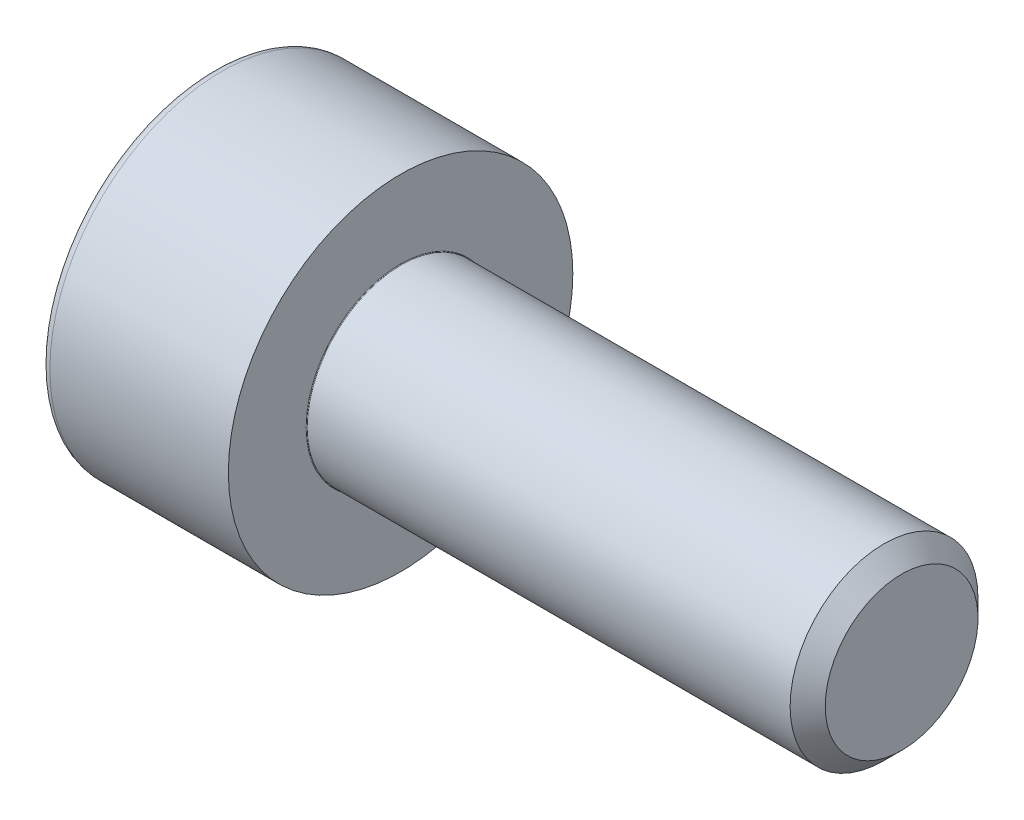
SolidWorks part; units mm, degrees
material "AISI 304"
ref_plane "Plane1" through (0, 0, 0) normal (0, 0, 1) x (1, 0, 0)
ref_plane "Plane2" through (0, 0, 0) normal (0, 1, 0) x (1, 0, 0)
ref_plane "Plane3" through (0, 0, 0) normal (1, 0, 0) x (0, 0, -1)
other "55"
sketch "BodySke" plane through (0, 0, 0) normal (0, 0, 1) x (1, 0, 0)
  line L0 (0, 0) -> (0, 2.75)
  line L1 (0, 2.75) -> (3, 2.75)
  line L2 (3, 2.75) -> (3, 1.5)
  line L3 (3, 1.5) -> (10.7195, 1.5)
  line L4 (11, 1.2195) -> (11, 0)
  line L5 (11, 0) -> (0, 0)
  line L6 (-31.75, 0) -> (127, 0) construction
  line L8 (11, 1.2195) -> (10.7195, 1.5)
  line L10 (11, -1.2195) -> (10.7195, -1.5) construction
  line L11 (3.5, 9.525) -> (3.5, 3.175) construction
  line L12 (3, 9.525) -> (3, 3.175) construction
  line L13 (-49, 9.525) -> (-49, 3.175) construction
  dimension "Head_ht" = 3
  dimension "Length" = 8
  dimension "Body_ch_ang" = 45
  dimension "Diameter" = 3
  dimension "Minor_dia" = 2.439
  dimension "Advance" = 0.5
  dimension "Thread_nom" = 8
  dimension "Thread_length" = 60
  dimension "Head_dia" = 5.5
revolve "Base-Revolve" add sketch "BodySke" angle 360 about L6
cosmetic thread "ThreadCosmetic" parameters "Thread_length"=6.5, "Thread_minor"=2.439
fillet "Fillet1" radius 0.01 1 edges at (3, 0, 1.5)
fillet "Fillet2" radius 0.15 1 edges at (0, 0, 2.75)
sketch "Sketch2" plane through (0, 0, 0) normal (0, 0, 1) x (1, 0, 0)
  line L0 (0, 1.28) -> (1.3, 1.28)
  line L1 (1.3, 1.28) -> (2.039, 0)
  line L2 (-31.75, 0) -> (127, 0) construction
  line L3 (2.039, 0) -> (0, 0)
  line L4 (0, 0) -> (0, 1.28)
  line L6 (0, 0) -> (47.625, 0) construction
  dimension "D1" = 1.28
  dimension "D2" = 60
  dimension "Depth" = 1.3
revolve "Hex-PreBroach" cut sketch "Sketch2" angle 360 about L6
sketch "Sketch3" plane through (0, 0, 0) normal (-1, 0, 0) x (0, 0.5, 0.866)
  line L0 (0.739, 1.28) -> (-0.739, 1.28)
  line L1 (-0.739, 1.28) -> (-1.478, 0)
  line L2 (0.739, 1.28) -> (1.478, 0)
  line L3 (0.739, -1.28) -> (1.478, 0)
  line L4 (0.739, -1.28) -> (-0.739, -1.28)
  line L5 (-0.739, -1.28) -> (-1.478, 0)
  dimension "D1" = 1.28
  dimension "D2" = 1.28
  dimension "Hex_size" = 2.56
extrude "Hex" cut sketch "Sketch3" against normal blind 1.3
sketch "ThdSchSke" plane through (0, 0, 0) normal (0, 0, 1) x (1, 0, 0)
  line L0 (4.5, -1.2195) -> (4.3036, -1.5)
  line L1 (4.5, -1.2195) -> (4.6964, -1.5)
  line L2 (4.6964, -1.5) -> (4.6964, -1.875)
  line L3 (-3.175, 0) -> (5.1513, 0) construction
  line L4 (0, 2.6) -> (0, -2.6) construction
  line L5 (4.6964, -1.875) -> (4.3036, -1.875)
  line L6 (4.3036, -1.875) -> (4.3036, -1.5)
  dimension "Thread_minor" = 2.439
  dimension "Diameter" = 3
  dimension "SideAngle" = 55
  dimension "VeeAngle" = 70
  dimension "Overcut" = 3.75
  dimension "Start" = 4.5
revolve "ThreadSchematic" [suppressed] cut sketch "ThdSchSke" angle 360 about L3
pattern_linear "ThdSchPat" [suppressed]
equation "\"D2@Sketch3\" = \"Hex_size@Sketch3\" / 2"
equation "\"D1@Sketch3\" = \"Hex_size@Sketch3\" / 2"
equation "\"D1@Sketch2\" = \"Hex_size@Sketch3\" / 2"
equation "\"Thread_minor@ThreadCosmetic\"  =  \"Minor_dia@BodySke\""
equation "\"Depth@Sketch2\" =  \"Key_eng@Hex\""
equation "\"Thread_length@ThreadCosmetic\" = ((sgn( (\"Length@BodySke\" - \"Advance@BodySke\" * 3.0) - \"Thread_nom@BodySke\" )-1)*( (\"Length@BodySke\" - \"Advance@BodySke\" * 3.0) - \"Thread_nom@BodySke\" ))/-2+ \"Thread_nom@BodySke\""
equation "\"Thread_minor@ThdSchSke\" = \"Minor_dia@BodySke\""
equation "\"Diameter@ThdSchSke\" = \"Diameter@BodySke\""
equation "\"Overcut@ThdSchSke\" = \"Diameter@BodySke\" * 1.25"
equation "\"Start@ThdSchSke\" = \"Head_ht@BodySke\" + \"Length@BodySke\" - \"Thread_length@ThreadCosmetic\"  '---Non-countersunk---"
equation "\"Num_threads@ThdSchPat\" = int( \"Thread_length@ThreadCosmetic\" / \"Advance@BodySke\" + 0.999 )  + 1"
equation "\"Advance@ThdSchPat\" = \"Thread_length@ThreadCosmetic\" /  (\"Num_threads@ThdSchPat\" - 1) 'relax it"
equation "\"Num_threads@ThdSchPat\" = \"Num_threads@ThdSchPat\" - sgn( \"Num_threads@ThdSchPat\" - 1) '---chamfered tips only---"
